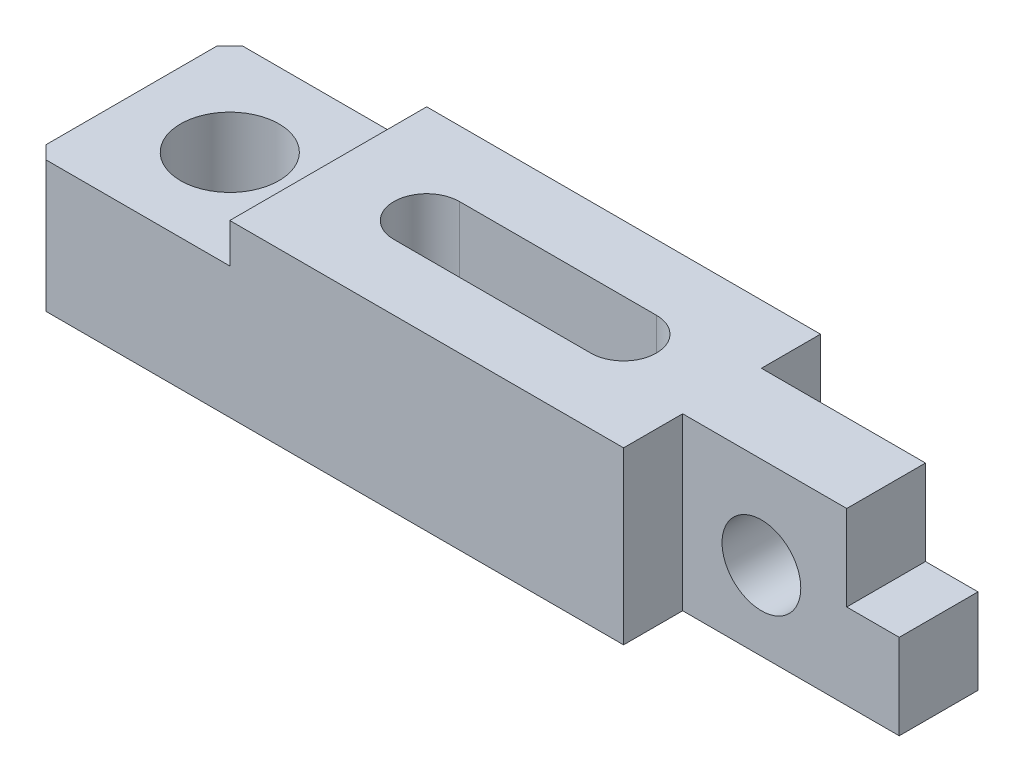
SolidWorks part; units mm, degrees
ref_plane "Piano frontale" through (0, 0, 0) normal (0, 0, 1) x (1, 0, 0)
ref_plane "Piano superiore" through (0, 0, 0) normal (0, 1, 0) x (1, 0, 0)
ref_plane "Piano destro" through (0, 0, 0) normal (1, 0, 0) x (0, 0, -1)
sketch "Schizzo1" plane through (0, 0, 0) normal (0, 0, 1) x (1, 0, 0)
  line L0 (0, 0) -> (0, 20)
  line L1 (30, 20) -> (30, 26)
  line L2 (30, 26) -> (115, 26)
  line L3 (115, 26) -> (115, 13)
  line L4 (115, 13) -> (123, 13)
  line L5 (123, 13) -> (123, 0)
  line L6 (123, 0) -> (0, 0)
  line L7 (0, 20) -> (30, 20)
  point P0 (123, 6.5)
  point P2 (0, 0)
  dimension "D1" = 123
  dimension "D2" = 26
  dimension "D3" = 6
  dimension "D4" = 30
  dimension "D5" = 8
  dimension "D6" = 13
extrude "Estrusione-Estrusione1" add sketch "Schizzo1" along normal mid plane 30
sketch "Schizzo5" plane through (0, 26, 0) normal (0, 1, 0) x (1, 0, 0)
  line L3 (123, 15) -> (90, 15)
  line L4 (115, 15) -> (30, 15) construction
  line L5 (90, 15) -> (90, 6)
  line L6 (90, 6) -> (123, 6)
  line L7 (123, -15) -> (123, 15) construction
  line L8 (123, 6) -> (123, 15)
  line L9 (123, -15) -> (123, -6)
  line L10 (123, -6) -> (90, -6)
  line L11 (90, -6) -> (90, -15)
  line L12 (115, -15) -> (30, -15) construction
  line L13 (90, -15) -> (123, -15)
  dimension "D1" = 33
  dimension "D2" = 9
  dimension "D3" = 9
  dimension "D4" = 33
extrude "Taglio-Estrusione1" cut sketch "Schizzo5" against normal up to next contours L8 L3 L5 L6 | L13 L9 L10 L11
sketch "Schizzo6" plane through (0, 26, 0) normal (0, 1, 0) x (1, 0, 0)
  line L0 (45, 0) -> (75, 0) construction
  line L1 (30, -15) -> (30, 15) construction
  line L2 (90, -6) -> (90, -15) construction
  line L3 (45, 0) -> (75, 0) construction
  line L4 (45, 5) -> (75, 5)
  line L5 (45, -5) -> (75, -5)
  arc A0 (45, 5) -> (45, -5) centre (45, 0) ccw
  arc A1 (75, -5) -> (75, 5) centre (75, 0) ccw
  point P7 (60, 0)
  dimension "D1" = 15
  dimension "D2" = 15
  dimension "D3" = 10
extrude "Taglio-Estrusione2" cut sketch "Schizzo6" against normal up to next
hole_wizard "Foro Ø15.0 (15)-2" positions "Schizzo3D25" profile "Schizzo27" hole size "Ø15.0" standard "ISO" end condition through all
sketch3d "Schizzo3D25"
  line L0 (0, 20, -15) -> (30, 20, 15) construction
  point P7 (15, 20, 0)
sketch "Schizzo27" plane through (15, 20, 0) normal (1, 0, 0) x (0, 0, 1)
  line L0 (0, 0) -> (0, 20)
  line L1 (0, 20) -> (7.5, 20)
  line L2 (7.5, 20) -> (7.5, 0)
  line L5 (7.5, 0) -> (0, 0)
  line L11 (0, -6.35) -> (0, 107.95) construction
  dimension "Thru Hole Dia." = 15
  dimension "Thru Hole Depth" = 20
hole_wizard "Foro Ø12.0 (12)-2" positions "Schizzo3D26" profile "Schizzo28" hole size "Ø12.0" standard "ISO" end condition up to next
sketch3d "Schizzo3D26"
  line L0 (123, 0, 6) -> (123, 13, 6) construction
  line L1 (90, 0, 6) -> (123, 0, 6) construction
  point P0 (102, 12, 6)
  dimension "D1" = 21
  dimension "D2" = 12
sketch "Schizzo28" plane through (102, 12, 6) normal (1, 0, 0) x (0, -1, 0)
  line L0 (0, 0) -> (0, 12)
  line L1 (0, 12) -> (6, 12)
  line L2 (6, 12) -> (6, 0)
  line L5 (6, 0) -> (0, 0)
  line L11 (0, -6.35) -> (0, 107.95) construction
  dimension "Thru Hole Dia." = 12
  dimension "Thru Hole Depth" = 12
chamfer "Smusso1" distance 2 angle 45 2 edges at (0, 10, 15) (0, 10, -15)
